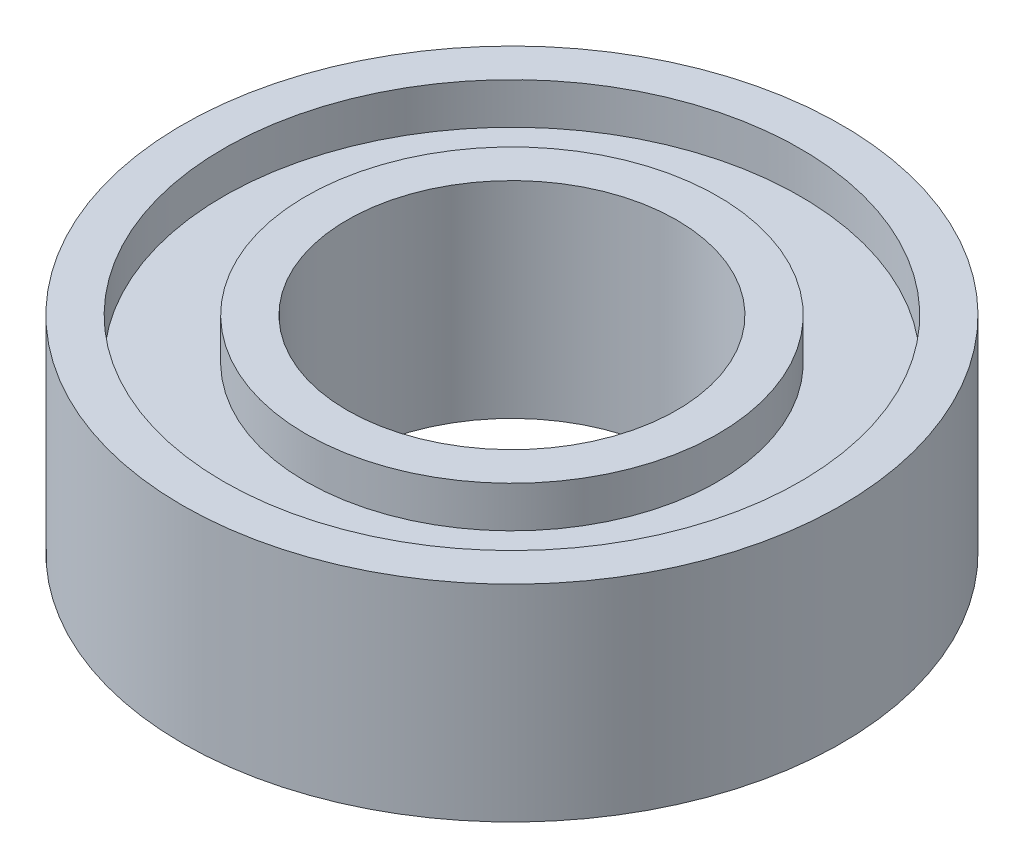
SolidWorks part; units mm, degrees
ref_plane "Front Plane" through (0, 0, 0) normal (0, 0, 1) x (1, 0, 0)
ref_plane "Top Plane" through (0, 0, 0) normal (0, 1, 0) x (1, 0, 0)
ref_plane "Right Plane" through (0, 0, 0) normal (1, 0, 0) x (0, 0, -1)
sketch "Sketch1" plane through (0, 0, 0) normal (0, 1, 0) x (1, 0, 0)
  circle A0 centre (0, 0) radius 8
  circle A1 centre (0, 0) radius 4
  dimension "D1" = 16
  dimension "D2" = 8
extrude "Boss-Extrude1" add sketch "Sketch1" along normal blind 5
sketch "Sketch2" plane through (0, 5, 0) normal (0, 1, 0) x (1, 0, 0)
  circle A0 centre (0, 0) radius 5
  circle A1 centre (0, 0) radius 7
  dimension "D1" = 14
  dimension "D2" = 10
extrude "Cut-Extrude1" cut sketch "Sketch2" against normal blind 1
sketch "Sketch3" plane through (0, 0, 0) normal (0, -1, 0) x (1, 0, 0)
  circle A0 centre (0, 0) radius 5
  circle A1 centre (0, 0) radius 7
  dimension "D1" = 14
  dimension "D2" = 10
extrude "Cut-Extrude2" cut sketch "Sketch3" against normal blind 1
